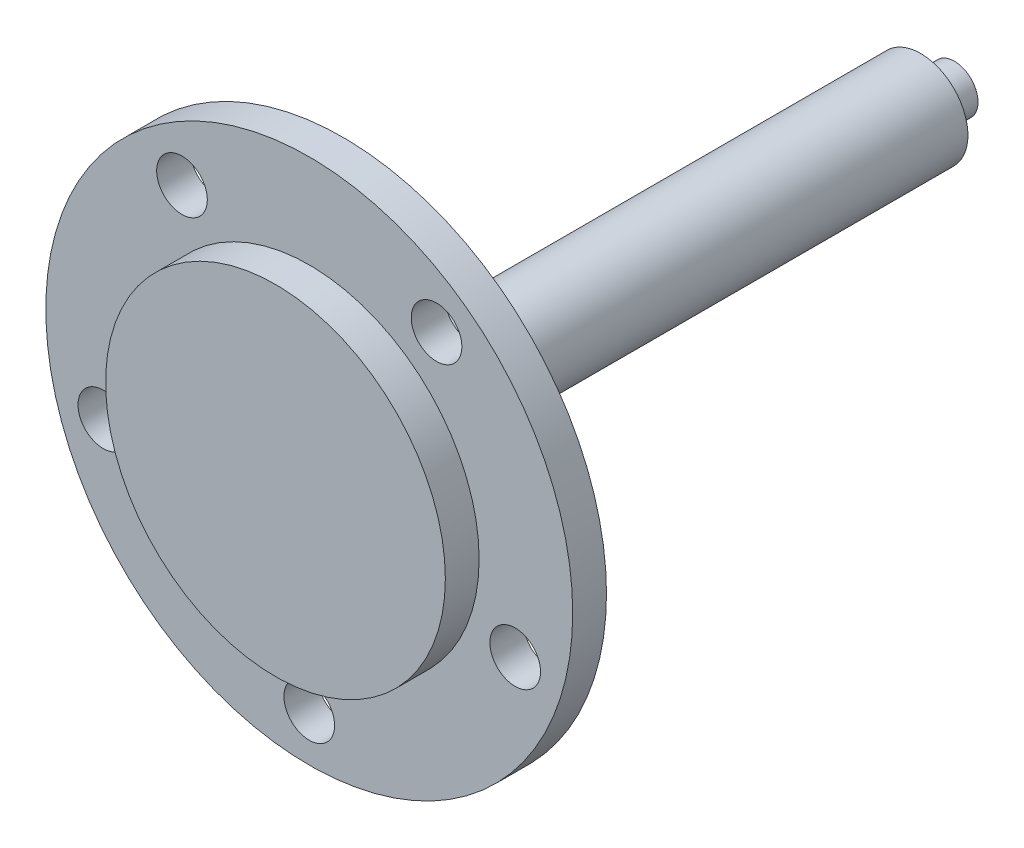
SolidWorks part; units mm, degrees
ref_plane "Front Plane" through (0, 0, 0) normal (0, 0, 1) x (1, 0, 0)
ref_plane "Top Plane" through (0, 0, 0) normal (0, 1, 0) x (1, 0, 0)
ref_plane "Right Plane" through (0, 0, 0) normal (1, 0, 0) x (0, 0, -1)
sketch "Sketch1" plane through (0, 0, 0) normal (0, 0, 1) x (1, 0, 0)
  circle A0 centre (0, 0) radius 14
extrude "Boss-Extrude2" add sketch "Sketch1" along normal blind 18 contours A0
sketch "Sketch8" plane through (0, 0, 0) normal (0, 0, -1) x (-1, 0, 0)
  circle A0 centre (0, 0) radius 14
extrude "Boss-Extrude7" add sketch "Sketch8" along normal blind 3
sketch "Sketch12" plane through (0, 0, 18) normal (0, 0, 1) x (1, 0, 0)
  circle A0 centre (0, 0) radius 14
extrude "Boss-Extrude11" add sketch "Sketch12" along normal blind 150
sketch "Sketch13" plane through (0, 0, -3) normal (0, 0, -1) x (-1, 0, 0)
  circle A0 centre (0, 0) radius 7
extrude "Boss-Extrude12" add sketch "Sketch13" along normal blind 10
sketch "Sketch14" plane through (0, 0, 168) normal (0, 0, 1) x (1, 0, 0)
  circle A0 centre (0, 0) radius 64.1077 construction
  circle A1 centre (0, -64.1077) radius 7.5
  circle A2 centre (-60.97, -19.8104) radius 7.5
  circle A3 centre (-37.6815, 51.8642) radius 7.5
  circle A4 centre (37.6815, 51.8642) radius 7.5
  circle A5 centre (60.97, -19.8104) radius 7.5
  circle A6 centre (0, 0) radius 78
  point P15 (0, 0)
  dimension "D1" = 5
  dimension "D2" = 156
extrude "Boss-Extrude13" add sketch "Sketch14" along normal blind 10
sketch "Sketch15" plane through (0, 0, 178) normal (0, 0, 1) x (1, 0, 0)
  circle A0 centre (0, 0) radius 50.2918
  dimension "D1" = 100.5836
extrude "Boss-Extrude14" add sketch "Sketch15" along normal blind 10
